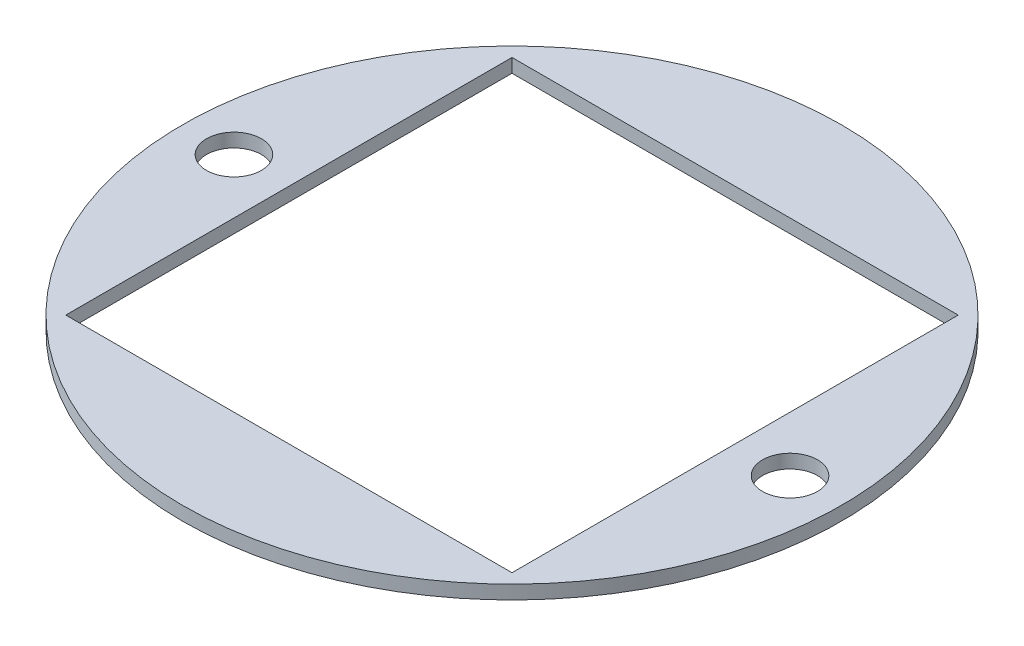
SolidWorks part; units mm, degrees
ref_plane "Front Plane" through (0, 0, 0) normal (0, 0, 1) x (1, 0, 0)
ref_plane "Top Plane" through (0, 0, 0) normal (0, 1, 0) x (1, 0, 0)
ref_plane "Right Plane" through (0, 0, 0) normal (1, 0, 0) x (0, 0, -1)
sketch "Sketch1" plane through (0, 0, 0) normal (0, 1, 0) x (1, 0, 0)
  circle A0 centre (0, 0) radius 76.2
  dimension "D1" = 152.4
extrude "Boss-Extrude1" add sketch "Sketch1" along normal blind 3.175
sketch "Sketch2" plane through (0, 3.175, 0) normal (0, 1, 0) x (1, 0, 0)
  circle A0 centre (0, 0) radius 35
  dimension "D1" = 70
extrude "Cut-Extrude1" cut sketch "Sketch2" against normal blind 3.175
sketch "Sketch3" plane through (0, 3.175, 0) normal (0, 1, 0) x (1, 0, 0)
  line L0 (-76.2, 0) -> (76.2, 0) construction
  line L1 (-51.5875, 51.5875) -> (51.5875, 51.5875) construction
  line L2 (-51.5875, 51.5875) -> (-51.5875, -51.5875) construction
  line L3 (-51.5875, -51.5875) -> (51.5875, -51.5875) construction
  line L4 (51.5875, 51.5875) -> (51.5875, -51.5875) construction
  circle A0 centre (0, 0) radius 76.2 construction
  circle A1 centre (-64.2875, 0) radius 6.35
  circle A2 centre (64.2875, 0) radius 6.35
  dimension "D1" = 12.7
  dimension "D2" = 12.7
  dimension "D3" = 12.7
  dimension "D4" = 12.7
extrude "Cut-Extrude2" cut sketch "Sketch3" against normal blind 10
sketch "Sketch4" plane through (0, 3.175, 0) normal (0, 1, 0) x (1, 0, 0)
  line L1 (50, -50) -> (-50, -50) construction
  line L2 (50, -50) -> (50, 50) construction
  line L3 (50, 50) -> (-50, 50) construction
  line L4 (-50, -50) -> (-50, 50) construction
  line L5 (50, -50) -> (-50, 50) construction
  line L6 (50, 50) -> (-50, -50) construction
  point P0 (0, 0)
  dimension "D1" = 100
  dimension "D2" = 100
sketch "Sketch5" plane through (0, 3.175, 0) normal (0, 1, 0) x (1, 0, 0)
  line L1 (50, -50) -> (-50, -50)
  line L2 (50, -50) -> (50, 50)
  line L3 (50, 50) -> (-50, 50)
  line L4 (-50, -50) -> (-50, 50)
  line L5 (50, -50) -> (-50, 50) construction
  line L6 (50, 50) -> (-50, -50) construction
  point P0 (0, 0)
extrude "Cut-Extrude3" cut sketch "Sketch5" against normal blind 10
fillet "Fillet1" radius 0.5 4 edges at (-50, 1.5875, 50) (50, 1.5875, 50) (50, 1.5875, -50) (-50, 1.5875, -50)
sketch "Sketch6" plane through (0, 3.175, 0) normal (0, 1, 0) x (1, 0, 0)
  line L0 (49.5, 50) -> (-49.5, 50) construction
  line L1 (51.5875, -51.5875) -> (-51.5875, -51.5875)
  line L2 (51.5875, -51.5875) -> (51.5875, 51.5875)
  line L3 (51.5875, 51.5875) -> (-51.5875, 51.5875)
  line L4 (-51.5875, -51.5875) -> (-51.5875, 51.5875)
  line L5 (51.5875, -51.5875) -> (-51.5875, 51.5875) construction
  line L6 (51.5875, 51.5875) -> (-51.5875, -51.5875) construction
  line L7 (-50, 49.5) -> (-50, -49.5) construction
  point P0 (0, 0)
  dimension "D1" = 1.5875
  dimension "D2" = 1.5875
extrude "Cut-Extrude4" cut sketch "Sketch6" against normal blind 10
